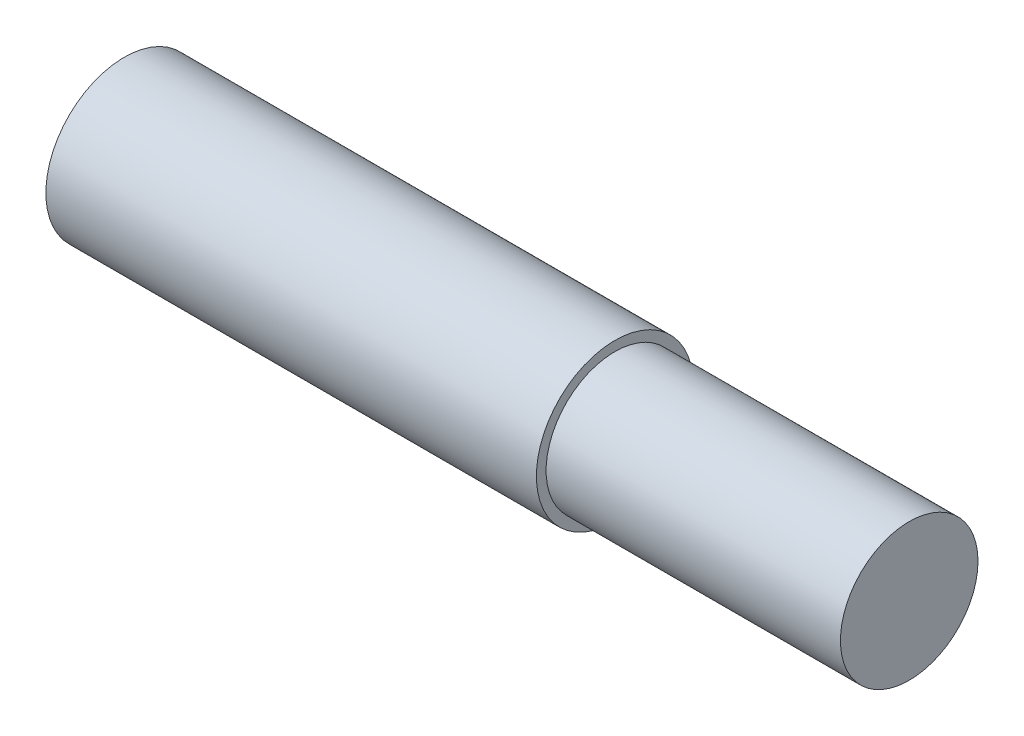
SolidWorks part; units mm, degrees
ref_plane "Front Plane" through (0, 0, 0) normal (0, 0, 1) x (1, 0, 0)
ref_plane "Top Plane" through (0, 0, 0) normal (0, 1, 0) x (1, 0, 0)
ref_plane "Right Plane" through (0, 0, 0) normal (1, 0, 0) x (0, 0, -1)
other "Bounding Box"
ref_plane "Default Plane" through (0, 5.4641, -1.4641) normal (0, -0.5, 0.866) x (1, 0, 0)
sketch "Sketch1" plane through (0, 0, 0) normal (1, 0, 0) x (0, 0, -1)
  circle A0 centre (0, 0) radius 4
extrude "Boss-Extrude1" add sketch "Sketch1" along normal blind 25 contours A0
sketch "Sketch2" plane through (0, 0, 0) normal (1, 0, 0) x (0, 0, -1)
  circle A0 centre (0, 0) radius 2.475
extrude "Cut-Extrude1" cut sketch "Sketch2" along normal blind 15
sketch "Sketch4" plane through (25, 0, 0) normal (1, 0, 0) x (0, 0, -1)
  circle A0 centre (0, 0) radius 3.5052
extrude "Boss-Extrude2" add sketch "Sketch4" along normal blind 15 contours A0
